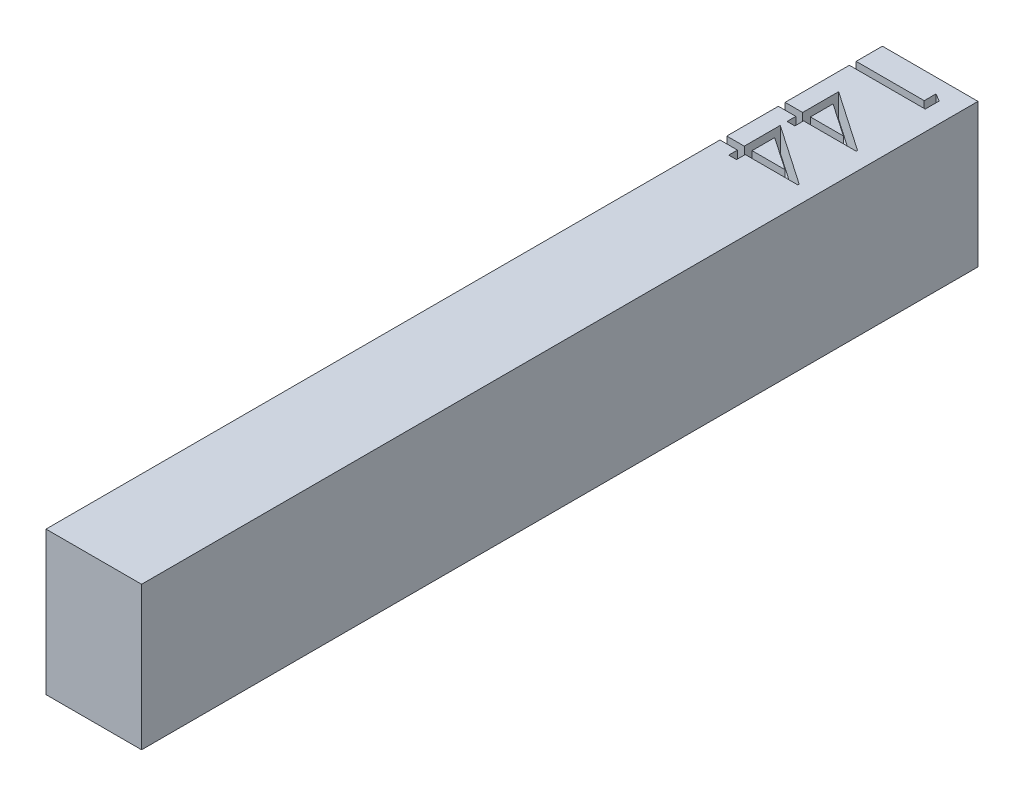
SolidWorks part; units mm, degrees
material "Acrylic (Medium-high impact)"
ref_plane "Front Plane" through (0, 0, 0) normal (0, 0, 1) x (1, 0, 0)
ref_plane "Top Plane" through (0, 0, 0) normal (0, 1, 0) x (1, 0, 0)
ref_plane "Right Plane" through (0, 0, 0) normal (1, 0, 0) x (0, 0, -1)
sketch "Sketch1" plane through (0, 0, 0) normal (0, 1, 0) x (1, 0, 0)
  line L1 (-2, 17.5) -> (2, 17.5)
  line L2 (-2, 17.5) -> (-2, -17.5)
  line L3 (-2, -17.5) -> (2, -17.5)
  line L4 (2, 17.5) -> (2, -17.5)
  line L5 (-2, 17.5) -> (2, -17.5) construction
  line L6 (-2, -17.5) -> (2, 17.5) construction
  point P0 (0, 0)
  dimension "D1" = 4
  dimension "D2" = 35
extrude "Boss-Extrude1" add sketch "Sketch1" along normal blind 6
sketch "Sketch3" plane through (0, 6, 0) normal (0, 1, 0) x (1, 0, 0)
  text T0 "144" font "Century Gothic" height 3.175
extrude "Cut-Extrude1" cut sketch "Sketch3" against normal blind 1
